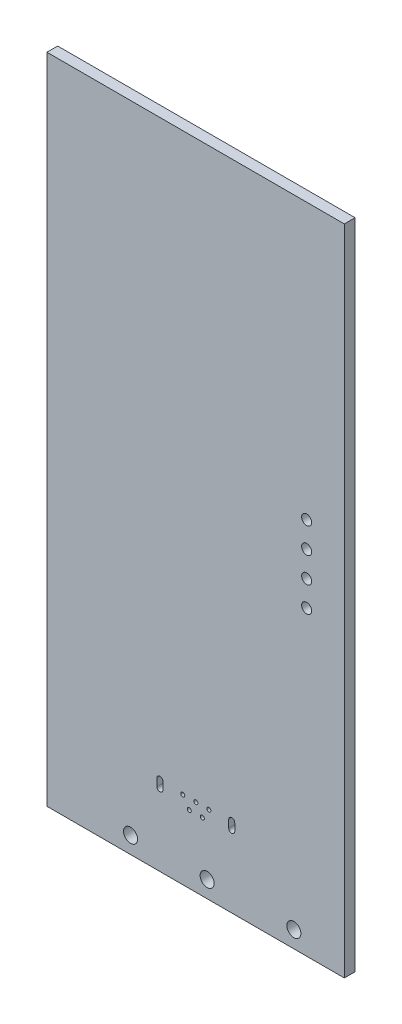
SolidWorks part; units mm, degrees
ref_plane "Спереди" through (0, 0, 0) normal (0, 0, 1) x (1, 0, 0)
ref_plane "Сверху" through (0, 0, 0) normal (0, 1, 0) x (1, 0, 0)
ref_plane "Справа" through (0, 0, 0) normal (1, 0, 0) x (0, 0, -1)
sketch "Эскиз1" plane through (0, 0, 0) normal (0, 0, 1) x (1, 0, 0)
  line L15 (86.681, 119.0866) -> (57.081, 119.0866)
  line L16 (57.081, 119.0866) -> (57.081, 54.0866)
  line L17 (57.081, 54.0866) -> (86.681, 54.0866)
  line L18 (86.681, 54.0866) -> (86.681, 119.0866)
  point P4 (86.3904, 118.7099)
  point P5 (58.4023, 118.7099)
  point P6 (58.4023, 55.0325)
  point P7 (87.0237, 55.0325)
  point P8 (86.5864, 55.0325)
  point P13 (0, 0)
  point P14 (86.181, 117.8711)
  point P15 (86.0011, 55.0325)
extrude "Board" add sketch "Эскиз1" along normal blind 1.0711
sketch "Эскиз13" plane through (0, 0, 1.0711) normal (0, 0, 1) x (1, 0, 0)
  circle A0 centre (82.931, 84.0926) radius 0.5
extrude "Hole - OLED1-4" cut sketch "Эскиз13" against normal blind 1.0711
sketch "Эскиз14" plane through (0, 0, 1.0711) normal (0, 0, 1) x (1, 0, 0)
  circle A0 centre (82.931, 86.6326) radius 0.5
extrude "Hole - OLED1-3" cut sketch "Эскиз14" against normal through all
sketch "Эскиз15" plane through (0, 0, 1.0711) normal (0, 0, 1) x (1, 0, 0)
  circle A0 centre (82.931, 89.1726) radius 0.5
extrude "Hole - OLED1-2" cut sketch "Эскиз15" against normal through all
sketch "Эскиз16" plane through (0, 0, 1.0711) normal (0, 0, 1) x (1, 0, 0)
  circle A0 centre (82.931, 91.7126) radius 0.5
extrude "Hole - OLED1-1" cut sketch "Эскиз16" against normal through all
sketch "Эскиз17" plane through (0, 0, 1.0711) normal (0, 0, 1) x (1, 0, 0)
  circle A0 centre (73.025, 55.753) radius 0.7
extrude "Hole - Free-4" cut sketch "Эскиз17" against normal through all
sketch "Эскиз18" plane through (0, 0, 1.0711) normal (0, 0, 1) x (1, 0, 0)
  circle A0 centre (81.661, 55.753) radius 0.7
extrude "Hole - Free-3" cut sketch "Эскиз18" against normal through all
sketch "Эскиз19" plane through (0, 0, 1.0711) normal (0, 0, 1) x (1, 0, 0)
  circle A0 centre (65.405, 55.753) radius 0.7
extrude "Hole - Free-2" cut sketch "Эскиз19" against normal through all
sketch "Эскиз21" plane through (0, 0, 1.0711) normal (0, 0, 1) x (1, 0, 0)
  line L0 (68.3259, 61.2566) -> (68.3259, 62.0066) construction
  line L1 (68.0259, 61.2566) -> (68.0259, 62.0066)
  line L2 (68.6259, 61.2566) -> (68.6259, 62.0066)
  arc A0 (68.0259, 61.2566) -> (68.6259, 61.2566) centre (68.3259, 61.2566) ccw
  arc A1 (68.6259, 62.0066) -> (68.0259, 62.0066) centre (68.3259, 62.0066) ccw
  point P2 (68.3259, 61.6316)
  point P7 (0, 0)
  point P8 (0, 0)
  point P9 (0, 0)
  point P10 (0, 0)
  point P11 (0, 0)
extrude "Hole - J1-6" cut sketch "Эскиз21" against normal through all
sketch "Эскиз23" plane through (0, 0, 1.0711) normal (0, 0, 1) x (1, 0, 0)
  line L0 (75.4759, 61.2566) -> (75.4759, 62.0066) construction
  line L1 (75.1759, 61.2566) -> (75.1759, 62.0066)
  line L2 (75.7759, 61.2566) -> (75.7759, 62.0066)
  arc A0 (75.1759, 61.2566) -> (75.7759, 61.2566) centre (75.4759, 61.2566) ccw
  arc A1 (75.7759, 62.0066) -> (75.1759, 62.0066) centre (75.4759, 62.0066) ccw
  point P2 (75.4759, 61.6316)
  point P7 (0, 0)
  point P8 (0, 0)
  point P9 (0, 0)
  point P10 (0, 0)
  point P11 (0, 0)
extrude "Hole - J1-7" cut sketch "Эскиз23" against normal through all
sketch "Эскиз24" plane through (0, 0, 1.0711) normal (0, 0, 1) x (1, 0, 0)
  circle A0 centre (70.6009, 61.8516) radius 0.2
extrude "Hole - J1-1" cut sketch "Эскиз24" against normal through all
sketch "Эскиз25" plane through (0, 0, 1.0711) normal (0, 0, 1) x (1, 0, 0)
  circle A0 centre (71.2509, 60.8516) radius 0.2
extrude "Hole - J1-2" cut sketch "Эскиз25" against normal through all
sketch "Эскиз26" plane through (0, 0, 1.0711) normal (0, 0, 1) x (1, 0, 0)
  circle A0 centre (71.9009, 61.8516) radius 0.2
extrude "Hole - J1-3" cut sketch "Эскиз26" against normal through all
sketch "Эскиз27" plane through (0, 0, 1.0711) normal (0, 0, 1) x (1, 0, 0)
  circle A0 centre (72.5509, 60.8516) radius 0.2
extrude "Hole - J1-4" cut sketch "Эскиз27" against normal through all
sketch "Эскиз28" plane through (0, 0, 1.0711) normal (0, 0, 1) x (1, 0, 0)
  circle A0 centre (73.2009, 61.8516) radius 0.2
extrude "Hole - J1-5" cut sketch "Эскиз28" against normal through all
